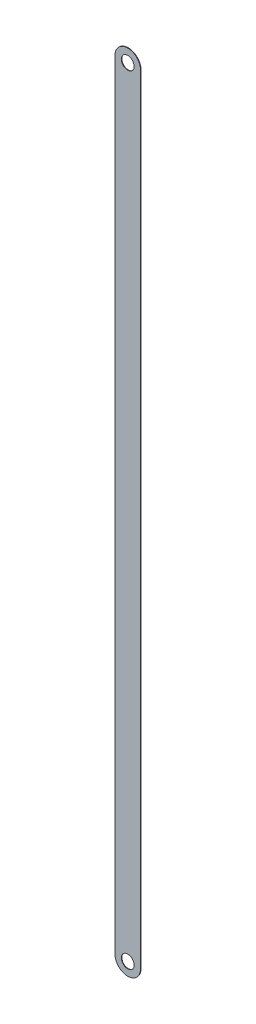
SolidWorks part; units mm, degrees
ref_plane "Front Plane" through (0, 0, 0) normal (0, 0, 1) x (1, 0, 0)
ref_plane "Top Plane" through (0, 0, 0) normal (0, 1, 0) x (1, 0, 0)
ref_plane "Right Plane" through (0, 0, 0) normal (1, 0, 0) x (0, 0, -1)
sketch "Sketch2" plane through (0, 0, 0) normal (0, 0, 1) x (1, 0, 0)
  line L0 (0, 386.08) -> (0, 0) construction
  line L1 (6.35, 386.08) -> (6.35, 0)
  line L2 (-6.35, 386.08) -> (-6.35, 0)
  arc A0 (6.35, 386.08) -> (-6.35, 386.08) centre (0, 386.08) ccw
  arc A1 (-6.35, 0) -> (6.35, 0) centre (0, 0) ccw
  circle A2 centre (0, 386.08) radius 3.175
  circle A3 centre (0, 0) radius 3.175
  point P3 (0, 193.04)
  dimension "D3" = 6.35
  dimension "D4" = 6.35
  dimension "D1" = 12.7
  dimension "D2" = 386.08
extrude "Boss-Extrude1" add sketch "Sketch2" along normal blind 0.254
